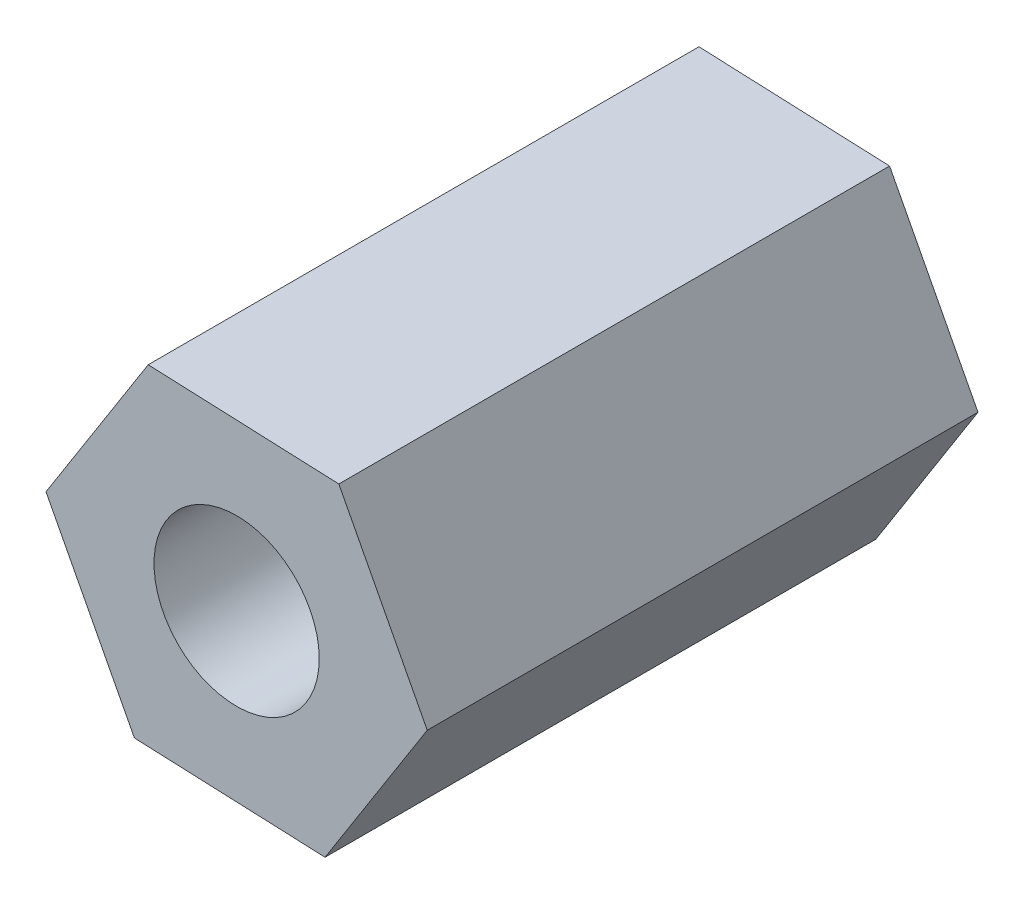
SolidWorks part; units mm, degrees
ref_plane "Front Plane" through (0, 0, 0) normal (0, 0, 1) x (1, 0, 0)
ref_plane "Top Plane" through (0, 0, 0) normal (0, 1, 0) x (1, 0, 0)
ref_plane "Right Plane" through (0, 0, 0) normal (1, 0, 0) x (0, 0, -1)
sketch "Sketch1" plane through (0, 0, 0) normal (0, 0, 1) x (1, 0, 0)
  line L1 (3.7116, 5.8501) -> (-3.2106, 6.1394)
  line L2 (-3.2106, 6.1394) -> (-6.9222, 0.2892)
  line L3 (-6.9222, 0.2892) -> (-3.7116, -5.8501)
  line L4 (-3.7116, -5.8501) -> (3.2106, -6.1394)
  line L5 (3.2106, -6.1394) -> (6.9222, -0.2892)
  line L6 (6.9222, -0.2892) -> (3.7116, 5.8501)
  circle A0 centre (0, 0) radius 6 construction
  dimension "D1" = 12
extrude "Boss-Extrude1" add sketch "Sketch1" along normal blind 20
sketch "Sketch2" plane through (0, 0, 20) normal (0, 0, 1) x (1, 0, 0)
  circle A0 centre (0, 0) radius 3
  dimension "D1" = 6
extrude "Cut-Extrude1" cut sketch "Sketch2" against normal through all
